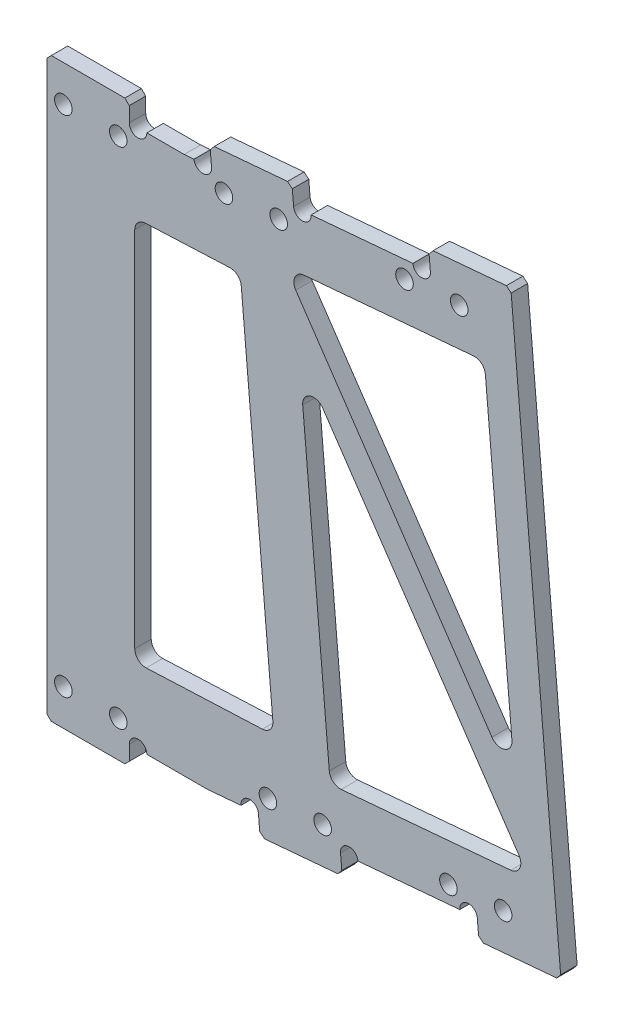
SolidWorks part; units mm, degrees
material "Thornel Mat VMA"
ref_plane "前视基准面" through (0, 0, 0) normal (0, 0, 1) x (1, 0, 0)
ref_plane "上视基准面" through (0, 0, 0) normal (0, 1, 0) x (1, 0, 0)
ref_plane "右视基准面" through (0, 0, 0) normal (1, 0, 0) x (0, 0, -1)
other "Configuration Table"
sketch "草图1" plane through (0, 0, 0) normal (0, 0, 1) x (1, 0, 0)
  line L0 (0, 0) -> (0, 98)
  line L1 (0, 98) -> (60, 98)
  line L2 (60, 98) -> (119.7717, 103.2293)
  line L3 (119.7717, 103.2293) -> (128.3129, 5.6023)
  line L4 (128.3129, 5.6023) -> (64.2788, 0)
  line L5 (64.2788, 0) -> (0, 0)
  line L6 (60, 98) -> (64.2788, 0) construction
  line L7 (60, 98) -> (68.5413, 0.3729) construction
  line L8 (60, 98) -> (60, 0) construction
  dimension "D1" = 5
  dimension "D2" = 87.5
  dimension "D3" = 98
  dimension "D4" = 60
  dimension "D5" = 60
extrude "凸台-拉伸1" add sketch "草图1" along normal blind 3
sketch "草图2" plane through (0, 0, 0) normal (0, 0, 1) x (1, 0, 0)
  line L0 (119.7717, 103.2293) -> (104.8288, 101.922)
  line L1 (119.7717, 103.2293) -> (119.4666, 106.716)
  line L2 (104.8288, 101.922) -> (104.5237, 105.4087)
  line L3 (119.4666, 106.716) -> (104.5237, 105.4087)
  line L4 (119.7717, 103.2293) -> (60, 98) construction
  line L5 (79.9239, 99.7431) -> (64.981, 98.4358)
  line L6 (79.9239, 99.7431) -> (79.6188, 103.2298)
  line L7 (64.981, 98.4358) -> (64.6759, 101.9225)
  line L8 (79.6188, 103.2298) -> (64.6759, 101.9225)
  line L9 (128.618, 2.1156) -> (113.6751, 0.8082)
  line L10 (128.618, 2.1156) -> (128.3129, 5.6023)
  line L11 (113.6751, 0.8082) -> (113.37, 4.2949)
  line L12 (128.3129, 5.6023) -> (113.37, 4.2949)
  line L13 (88.7702, -1.3706) -> (73.8273, -2.678)
  line L14 (88.7702, -1.3706) -> (88.4652, 2.116)
  line L15 (73.8273, -2.678) -> (73.5222, 0.8087)
  line L16 (88.4652, 2.116) -> (73.5222, 0.8087)
  line L17 (64.2788, 0) -> (128.3129, 5.6023) construction
  dimension "D1" = 15
  dimension "D2" = 3.5
  dimension "D4" = 25
  dimension "D3" = 2
  dimension "D5" = 2
extrude "凸台-拉伸2" add sketch "草图2" along normal through all
sketch "草图3" plane through (0, 0, 0) normal (0, 0, 1) x (1, 0, 0)
  line L2 (104.8288, 101.922) -> (79.9239, 99.7431) construction
  line L3 (101.6409, 101.6431) -> (104.8288, 101.922)
  line L4 (79.9239, 99.7431) -> (83.1117, 100.022)
  line L5 (61.7932, 98.1569) -> (64.981, 98.4358)
  line L7 (124.0423, 54.4158) -> (70.4309, 49.7254) construction
  line L8 (128.618, 2.1156) -> (119.4666, 106.716) construction
  line L10 (64.981, 98.4358) -> (60, 98) construction
  line L11 (70.3344, 0.5298) -> (73.5222, 0.8087)
  line L12 (88.4652, 2.116) -> (91.653, 2.3949)
  line L13 (110.1822, 4.016) -> (113.37, 4.2949)
  line L14 (104.5237, 105.4087) -> (104.8288, 101.922) construction
  line L15 (110.0799, 99.2696) -> (100.118, 98.398) construction
  line L16 (110.0799, 99.2696) -> (77.2055, 96.3934) construction
  line L17 (104.8288, 101.922) -> (79.9239, 99.7431) construction
  arc A1 (104.8288, 101.922) -> (101.6409, 101.6431) centre (103.2348, 101.7826) cw
  arc A2 (83.1117, 100.022) -> (79.9239, 99.7431) centre (81.5178, 99.8826) cw
  arc A3 (64.981, 98.4358) -> (61.7932, 98.1569) centre (63.3871, 98.2963) cw
  arc A4 (73.5222, 0.8087) -> (70.3344, 0.5298) centre (71.9283, 0.6692) ccw
  arc A5 (91.653, 2.3949) -> (88.4652, 2.116) centre (90.0591, 2.2555) ccw
  arc A6 (113.37, 4.2949) -> (110.1822, 4.016) centre (111.7761, 4.1555) ccw
  circle A7 centre (110.0799, 99.2696) radius 1.6
  circle A8 centre (100.118, 98.398) radius 1.6
  circle A9 centre (77.2055, 96.3934) radius 1.6
  circle A10 centre (67.2435, 95.5219) radius 1.6
  circle A11 centre (118.0808, 7.8189) radius 1.6
  circle A12 centre (108.1189, 6.9474) radius 1.6
  circle A13 centre (85.2064, 4.9428) radius 1.6
  circle A14 centre (75.2444, 4.0712) radius 1.6
  point P19 (124.0423, 54.4158)
  dimension "D3" = 1.6
  dimension "D4" = 3.2
  dimension "D5" = 3.2
  dimension "D6" = 10
  dimension "D8" = 23
  dimension "D10" = 10
  dimension "D9" = 3.1
  dimension "D1" = 2
  dimension "D2" = 2
  dimension "D7" = 2
extrude "切除-拉伸1" cut sketch "草图3" along normal through all
sketch "草图4" plane through (0, 0, 0) normal (0, 0, 1) x (1, 0, 0)
  line L0 (35, 98) -> (50, 98)
  line L1 (0, 98) -> (15, 98)
  line L2 (0, 98) -> (0, 101.5)
  line L3 (0, 101.5) -> (15, 101.5)
  line L4 (15, 98) -> (15, 101.5)
  line L5 (35, 98) -> (35, 101.5)
  line L6 (35, 101.5) -> (50, 101.5)
  line L7 (50, 98) -> (50, 101.5)
  line L8 (0, 49) -> (43.292, 49) construction
  line L10 (50, 0) -> (50, -3.5)
  line L11 (35, -3.5) -> (50, -3.5)
  line L12 (35, 0) -> (35, -3.5)
  line L13 (15, 0) -> (15, -3.5)
  line L14 (0, -3.5) -> (15, -3.5)
  line L15 (0, 0) -> (0, -3.5)
  line L16 (0, 0) -> (15, 0)
  line L17 (35, 0) -> (50, 0)
  dimension "D2" = 20
  dimension "D3" = 15
  dimension "D4" = 3.5
  dimension "D1" = 2
extrude "凸台-拉伸3" add sketch "草图4" along normal through all
sketch "草图5" plane through (0, 0, 0) normal (0, 0, 1) x (1, 0, 0)
  line L0 (35, 98) -> (15, 98) construction
  line L1 (15, 98) -> (18.2, 98)
  line L2 (31.8, 98) -> (35, 98)
  line L3 (50, 98) -> (53.2, 98)
  line L4 (50, 98) -> (50, 101.5) construction
  line L5 (0, 49) -> (29.0579, 49) construction
  line L7 (50, 0) -> (53.2, 0)
  line L8 (31.8, 0) -> (35, 0)
  line L9 (15, 0) -> (18.2, 0)
  line L10 (3, 94.9) -> (13, 94.9) construction
  line L11 (0, 101.5) -> (0, -3.5) construction
  arc A0 (15, 98) -> (18.2, 98) centre (16.6, 98) ccw
  arc A1 (31.8, 98) -> (35, 98) centre (33.4, 98) ccw
  arc A2 (50, 98) -> (53.2, 98) centre (51.6, 98) ccw
  arc A3 (50, 0) -> (53.2, 0) centre (51.6, 0) cw
  arc A4 (31.8, 0) -> (35, 0) centre (33.4, 0) cw
  arc A5 (15, 0) -> (18.2, 0) centre (16.6, 0) cw
  circle A6 centre (3, 94.9) radius 1.6
  circle A7 centre (13, 94.9) radius 1.6
  circle A8 centre (38, 94.9) radius 1.6
  circle A9 centre (48, 94.9) radius 1.6
  circle A10 centre (3, 3.1) radius 1.6
  circle A11 centre (13, 3.1) radius 1.6
  circle A12 centre (48, 3.1) radius 1.6
  circle A13 centre (38, 3.1) radius 1.6
  dimension "D3" = 1.6
  dimension "D6" = 3.2
  dimension "D7" = 3
  dimension "D9" = 2
  dimension "D10" = 25
  dimension "D5" = 10
  dimension "D8" = 3.1
  dimension "D1" = 2
  dimension "D2" = 2
  dimension "D4" = 2
extrude "切除-拉伸2" cut sketch "草图5" along normal through all
chamfer "倒角1" distance 0.8 angle 45 16 edges at (73.8273, -2.678, 1.5) (88.7702, -1.3706, 1.5) (113.6751, 0.8082, 1.5) (128.618, 2.1156, 1.5) (119.4666, 106.716, 1.5) (104.5237, 105.4087, 1.5) (79.6188, 103.2298, 1.5) (64.6759, 101.9225, 1.5) (15, -3.5, 1.5) (50, -3.5, 1.5) (35, -3.5, 1.5) (0, -3.5, 1.5) (0, 101.5, 1.5) (50, 101.5, 1.5) (35, 101.5, 1.5) (15, 101.5, 1.5)
sketch "草图6" plane through (0, 0, 0) normal (0, 0, 1) x (1, 0, 0)
  line L10 (88.5898, 12.1651) -> (119.4718, 14.867)
  line L11 (86.4231, 13.9832) -> (81.5829, 69.307)
  line L12 (119.6806, 35.4283) -> (114.8404, 90.7521)
  line L13 (81.7916, 89.8683) -> (112.6737, 92.5702)
  line L14 (91.653, 2.3949) -> (110.1822, 4.016) construction
  line L15 (80.3112, 86.7526) -> (116.0335, 34.1307)
  line L16 (85.23, 70.6046) -> (120.9523, 17.9827)
  line L17 (128.5483, 2.9125) -> (119.5364, 105.9191) construction
  line L18 (101.6409, 101.6431) -> (83.1117, 100.022) construction
  line L19 (60, 98) -> (64.2788, 0) construction
  line L20 (53.2, 0) -> (64.2788, 0) construction
  line L21 (64.2788, 0) -> (70.3344, 0.5298) construction
  line L22 (51, 81.6324) -> (51, 15.5695)
  line L23 (70.3923, 82.4791) -> (76.15, 16.6676)
  line L24 (52.9128, 83.6305) -> (68.3127, 84.3029)
  line L25 (53.0872, 13.5714) -> (74.2449, 14.4952)
  arc A6 (120.9523, 17.9827) -> (119.4718, 14.867) centre (119.2975, 16.8594) cw
  arc A7 (86.4231, 13.9832) -> (88.5898, 12.1651) centre (88.4155, 14.1575) ccw
  arc A8 (85.23, 70.6046) -> (81.5829, 69.307) centre (83.5753, 69.4813) ccw
  arc A9 (116.0335, 34.1307) -> (119.6806, 35.4283) centre (117.6882, 35.254) ccw
  arc A10 (114.8404, 90.7521) -> (112.6737, 92.5702) centre (112.848, 90.5778) ccw
  arc A11 (80.3112, 86.7526) -> (81.7916, 89.8683) centre (81.966, 87.8759) cw
  arc A12 (51, 81.6324) -> (52.9128, 83.6305) centre (53, 81.6324) cw
  arc A13 (70.3923, 82.4791) -> (68.3127, 84.3029) centre (68.3999, 82.3048) ccw
  arc A14 (76.15, 16.6676) -> (74.2449, 14.4952) centre (74.1577, 16.4933) cw
  arc A15 (51, 15.5695) -> (53.0872, 13.5714) centre (53, 15.5695) ccw
  point P52 (100.9176, 3.2055)
  point P66 (51, 83.547)
  point P69 (70.2254, 84.3864)
  point P72 (76.3321, 14.5863)
  point P75 (51, 13.4803)
  dimension "D6" = 2
  dimension "D7" = 6
  dimension "D8" = 10
  dimension "D9" = 10
  dimension "D10" = 35
  dimension "D12" = 5
extrude "切除-拉伸3" cut sketch "草图6" along normal through all
sketch "草图7" plane through (0, 0, 3) normal (0, 0, 1) x (1, 0, 0)
  line L0 (35, 98) -> (35, 0)
  line L1 (35, 98) -> (16.5491, 104.6903)
  line L2 (16.5491, 104.6903) -> (-5.587, 104.6903)
  line L3 (-5.587, 104.6903) -> (-16.7497, 87.3788)
  line L4 (-16.7497, 87.3788) -> (-17.7903, 82.365)
  line L5 (-17.7903, 82.365) -> (-15.0469, 45.8499)
  line L6 (-15.0469, 45.8499) -> (-13.4387, -4.0982)
  line L7 (-13.4387, -4.0982) -> (11.7245, -8.166)
  line L8 (11.7245, -8.166) -> (27.8063, -5.328)
  line L9 (27.8063, -5.328) -> (35, 0)
extrude "切除-拉伸4" cut sketch "草图7" against normal blind 10
